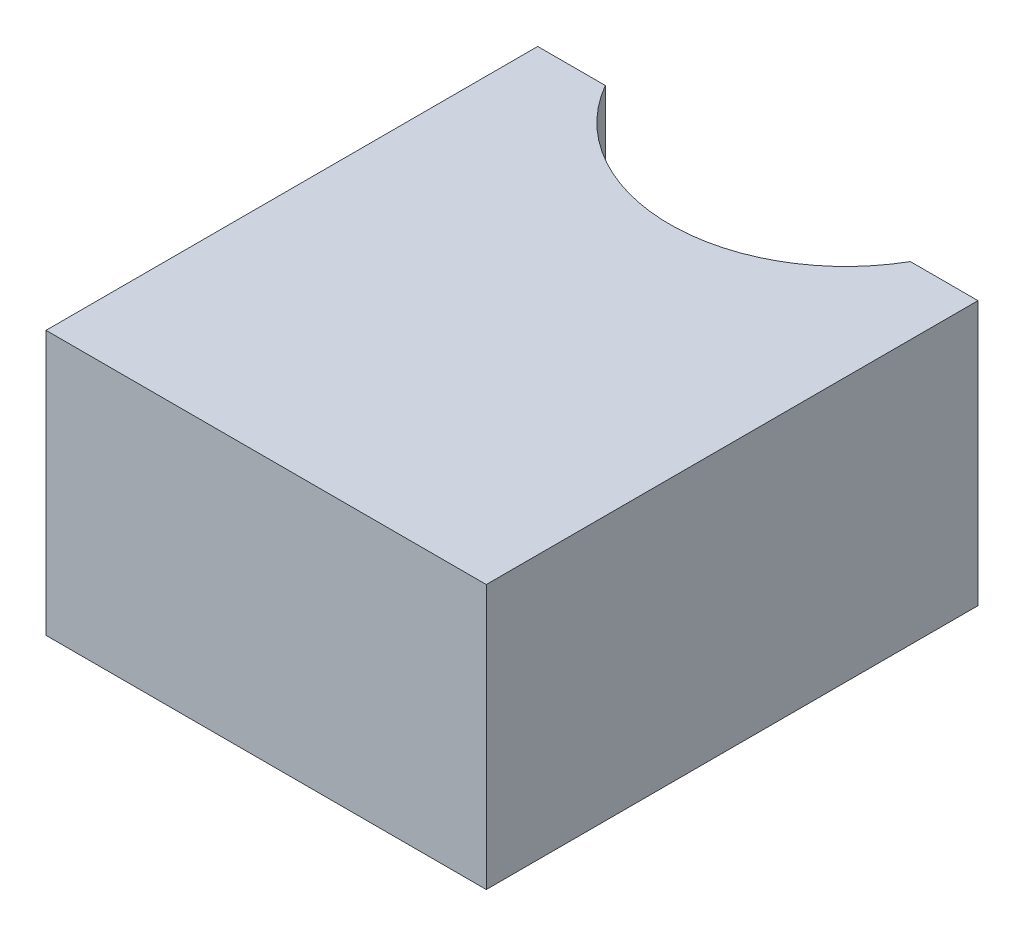
SolidWorks part; units mm, degrees
material "Custom Plastic"
ref_plane "X-Y Datum" through (0, 0, 0) normal (0, 0, 1) x (1, 0, 0)
ref_plane "X-Z Datum" through (0, 0, 0) normal (0, 1, 0) x (1, 0, 0)
ref_plane "Y-Z Datum" through (0, 0, 0) normal (1, 0, 0) x (0, 0, -1)
sketch "Sketch1" plane through (0, 0, 0) normal (0, 0, 1) x (1, 0, 0)
  line L1 (-15.875, 9.525) -> (15.875, 9.525)
  line L2 (-15.875, 9.525) -> (-15.875, -9.525)
  line L3 (-15.875, -9.525) -> (15.875, -9.525)
  line L4 (15.875, 9.525) -> (15.875, -9.525)
  line L5 (-15.875, 9.525) -> (15.875, -9.525) construction
  line L6 (-15.875, -9.525) -> (15.875, 9.525) construction
  point P0 (0, 0)
  dimension "D1" = 31.75
  dimension "D2" = 19.05
extrude "Boss-Extrude1" add sketch "Sketch1" along normal blind 35.4584
sketch "Sketch2" plane through (0, 9.525, 0) normal (0, 1, 0) x (1, 0, 0)
  circle A0 centre (0, 6.35) radius 12.7
  point P2 (0, -6.35)
  dimension "D1" = 25.4
  dimension "D2" = 6.35
extrude "Cut-Extrude1" cut sketch "Sketch2" against normal through all
